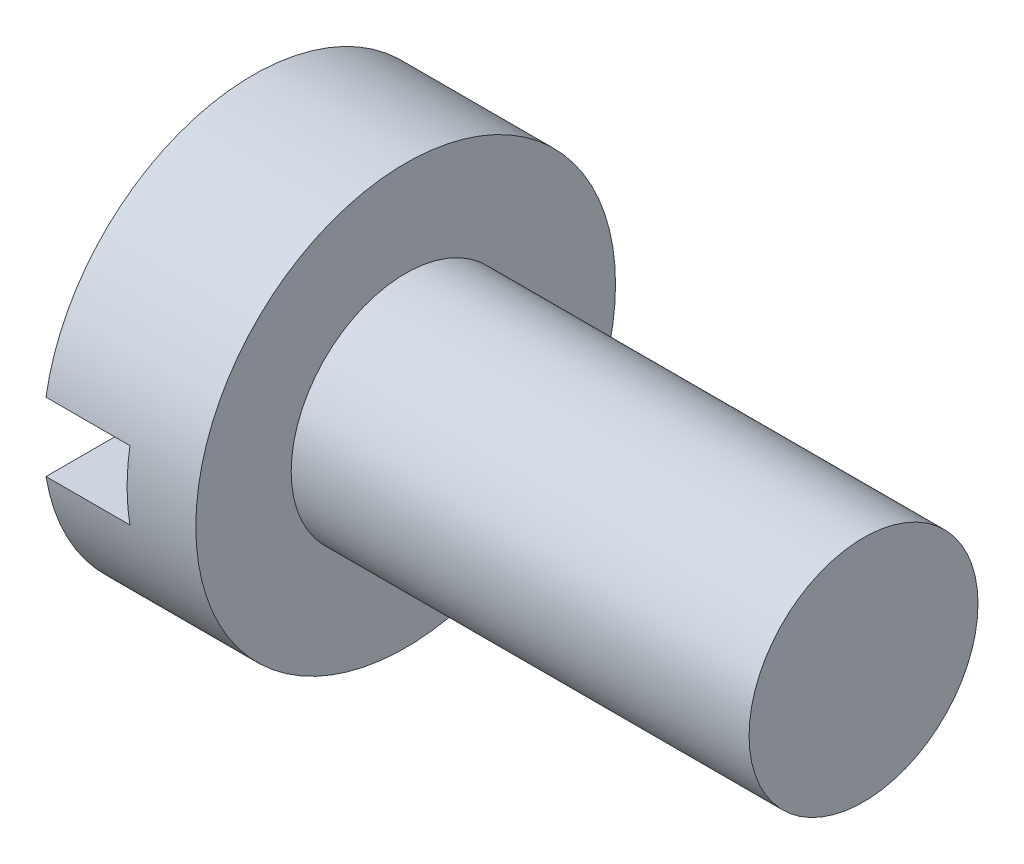
SolidWorks part; units mm, degrees
ref_plane "Plane1" through (0, 0, 0) normal (0, 0, 1) x (1, 0, 0)
ref_plane "Plane2" through (0, 0, 0) normal (0, 1, 0) x (1, 0, 0)
ref_plane "Plane3" through (0, 0, 0) normal (1, 0, 0) x (0, 0, -1)
sketch "BodySke" plane through (0, 0, 0) normal (0, 0, 1) x (1, 0, 0)
  line L0 (2, 1.5) -> (2, 2.75)
  line L1 (0, 0) -> (0, 2.75)
  line L2 (-25.4, 0) -> (127, 0) construction
  line L3 (8, 0) -> (0, 0)
  line L4 (2, 1.5) -> (8, 1.5)
  line L5 (8, 1.5) -> (8, 0)
  line L6 (0, 2.75) -> (2, 2.75)
  line L9 (2.5, 3.0875) -> (2.5, -6.4375) construction
  line L10 (2, 6.35) -> (2, -3.175) construction
  dimension "Length" = 6
  dimension "Head_ht" = 2
  dimension "Advance" = 0.5
  dimension "Thread_nom" = 6
  dimension "Head_dia" = 5.5
  dimension "Diameter" = 3
revolve "Base-Revolve" add sketch "BodySke" angle 360 about L2
cosmetic thread "ThreadCosmetic" parameters "Thread_length"=5, "Thread_minor"=2.459
sketch "Sketch2" plane through (0, 0, 0) normal (1, 0, 0) x (0, 0, -1)
  line L0 (2.75, -0.45) -> (-2.75, -0.45)
  line L1 (2.75, -0.45) -> (2.75, 0.45)
  line L2 (-2.75, 0.45) -> (2.75, 0.45)
  line L3 (-2.75, 0.45) -> (-2.75, -0.45)
  dimension "D1" = 5.5
  dimension "Slot_width" = 0.9
  dimension "D2" = 2.75
  dimension "D3" = 0.45
extrude "Slot" cut sketch "Sketch2" along normal blind 1.1
equation "\"D1@Sketch2\" = \"Head_dia@BodySke\""
equation "\"D2@Sketch2\" = \"D1@Sketch2\" / 2"
equation "\"D3@Sketch2\" = \"Slot_width@Sketch2\" / 2"
equation "\"Thread_length@ThreadCosmetic\" = ((sgn( (\"Length@BodySke\" - \"Advance@BodySke\" * 2.0 ) - \"Thread_nom@BodySke\" )-1)*( (\"Length@BodySke\" - \"Advance@BodySke\"  * 2.0) - \"Thread_nom@BodySke\" ))/-2+ \"Thread_nom@BodySke\""
